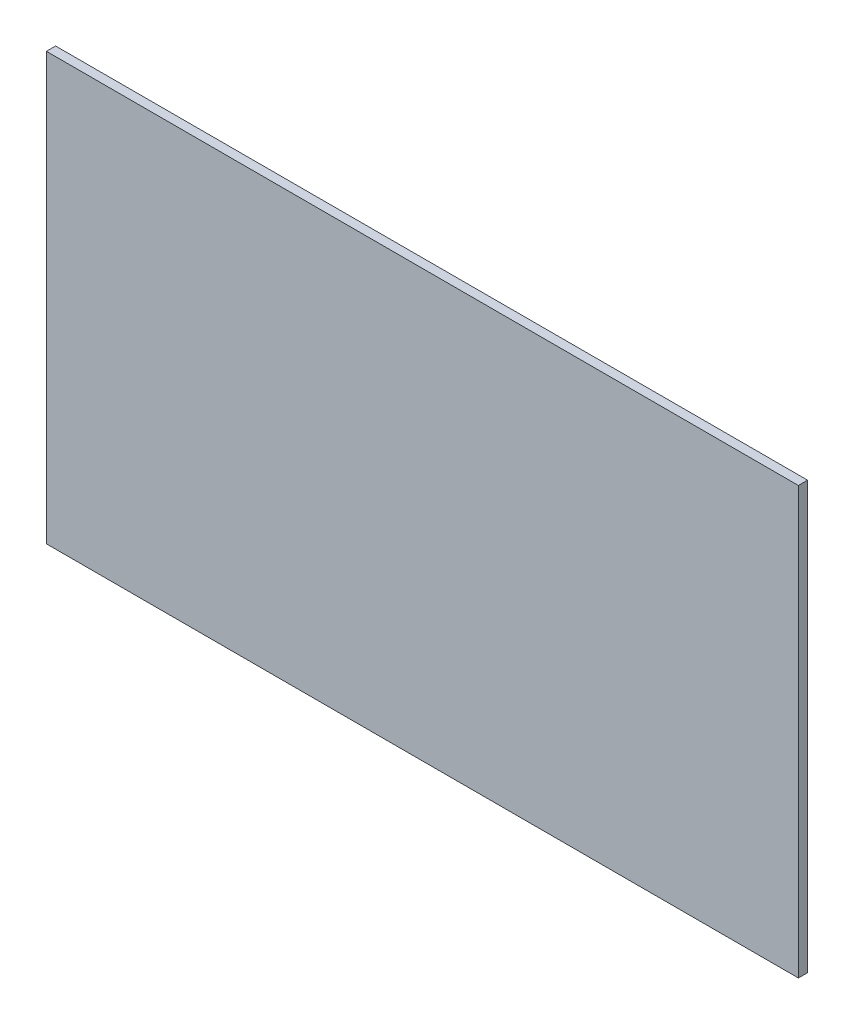
SolidWorks part; units mm, degrees
ref_plane "Front Plane" through (0, 0, 0) normal (0, 0, 1) x (1, 0, 0)
ref_plane "Top Plane" through (0, 0, 0) normal (0, 1, 0) x (1, 0, 0)
ref_plane "Right Plane" through (0, 0, 0) normal (1, 0, 0) x (0, 0, -1)
sketch "Sketch1" plane through (0, 0, 0) normal (0, 0, 1) x (1, 0, 0)
  line L1 (0, 0) -> (2045, 0)
  line L2 (0, 0) -> (0, 1160)
  line L3 (0, 1160) -> (2045, 1160)
  line L4 (2045, 0) -> (2045, 1160)
  dimension "D1" = 1160
  dimension "D2" = 2045
extrude "Boss-Extrude1" add sketch "Sketch1" along normal blind 25
